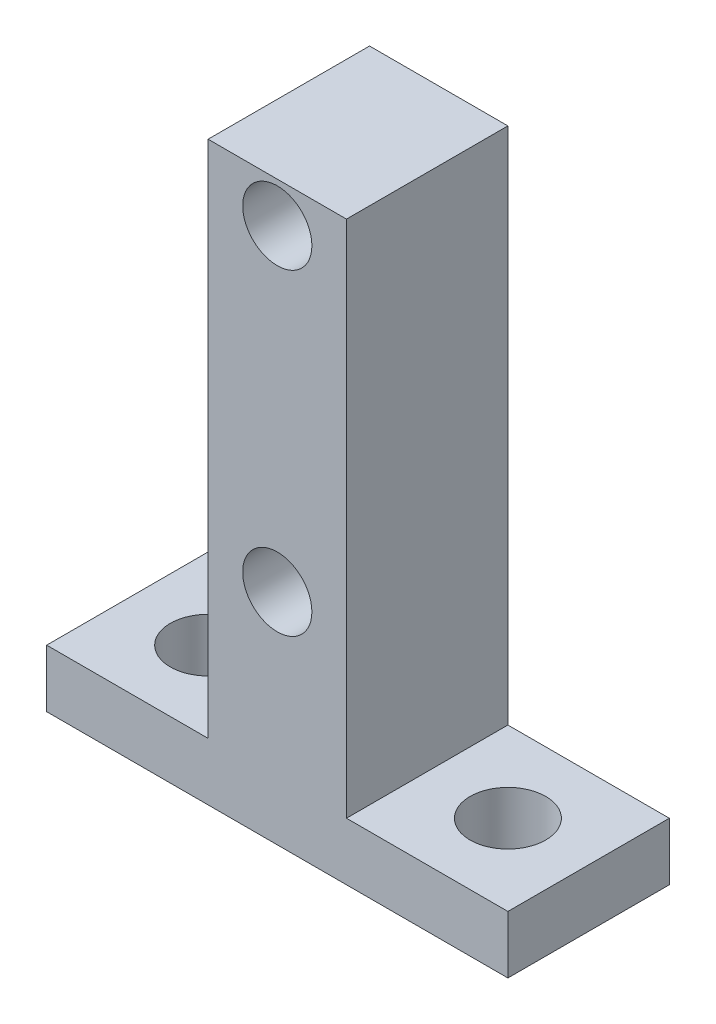
SolidWorks part; units mm, degrees
ref_plane "Front Plane" through (0, 0, 0) normal (0, 0, 1) x (1, 0, 0)
ref_plane "Top Plane" through (0, 0, 0) normal (0, 1, 0) x (1, 0, 0)
ref_plane "Right Plane" through (0, 0, 0) normal (1, 0, 0) x (0, 0, -1)
sketch "Sketch1" plane through (0, 0, 0) normal (0, 0, 1) x (1, 0, 0)
  line L0 (-37.3856, -8.255) -> (-37.3856, -3.175)
  line L1 (-37.3856, 3.175) -> (37.3856, 3.175)
  line L2 (-37.3856, 3.175) -> (-37.3856, -3.175)
  line L3 (-27.5431, -3.175) -> (37.3856, -3.175)
  line L4 (37.3856, 3.175) -> (37.3856, -3.175)
  line L5 (-37.3856, 3.175) -> (37.3856, -3.175) construction
  line L6 (-37.3856, -3.175) -> (37.3856, 3.175) construction
  line L7 (-27.5431, -8.255) -> (-27.5431, -3.175)
  circle A0 centre (-32.4644, -8.255) radius 2.3812
  arc A1 (-37.3856, -8.255) -> (-27.5431, -8.255) centre (-32.4644, -8.255) ccw
  point P0 (0, 0)
  dimension "D1" = 4.7625
  dimension "D3" = 2.54
  dimension "D2" = 6.35
  dimension "D4" = 69.85
  dimension "D5" = 5.08
extrude "Boss-Extrude1" add sketch "Sketch1" along normal blind 38.1
fillet "Fillet1" radius 6.35 1 edges at (-37.3856, 3.175, 19.05)
sketch "Sketch3" plane through (37.3856, 0, 0) normal (1, 0, 0) x (0, 0, -1)
  line L4 (0, -3.175) -> (0, 3.175)
  line L5 (0, 3.175) -> (-38.1, 3.175)
  line L6 (-38.1, 3.175) -> (-38.1, -3.175)
  line L7 (-38.1, -3.175) -> (0, -3.175)
  line L8 (0, -3.175) -> (0, 3.175)
  line L9 (0, 3.175) -> (-38.1, 3.175)
  line L10 (-38.1, 3.175) -> (-38.1, -3.175)
  line L11 (-38.1, -3.175) -> (0, -3.175)
  dimension "D1" = 0
extrude "Boss-Extrude2" add sketch "Sketch3" along normal blind 12.7
sketch "Sketch2" plane through (0, 3.175, 0) normal (0, 1, 0) x (1, 0, 0)
  line L1 (48.4981, -15.875) -> (11.9856, -15.875) construction
  line L2 (48.4981, -15.875) -> (48.4981, 0) construction
  line L3 (48.4981, 0) -> (11.9856, 0) construction
  line L4 (11.9856, -15.875) -> (11.9856, 0) construction
  line L5 (48.4981, -15.875) -> (11.9856, 0) construction
  line L6 (48.4981, 0) -> (11.9856, -15.875) construction
  line L7 (11.9856, -17.4625) -> (-16.5894, -17.4625) construction
  line L8 (11.9856, -17.4625) -> (11.9856, 1.5875) construction
  line L9 (11.9856, 1.5875) -> (-16.5894, 1.5875) construction
  line L10 (-16.5894, -17.4625) -> (-16.5894, 1.5875) construction
  line L11 (11.9856, -17.4625) -> (-16.5894, 1.5875) construction
  line L12 (11.9856, 1.5875) -> (-16.5894, -17.4625) construction
  line L13 (37.3856, -25.4) -> (37.3856, 9.525) construction
  line L14 (50.0856, 0) -> (-31.0356, 0) construction
  line L15 (-34.8456, -38.1) -> (-30.0831, -38.1) construction
  line L16 (-34.8456, -38.1) -> (-30.0831, -38.1) construction
  line L18 (21.3519, -24.765) -> (13.7319, -24.765)
  line L19 (21.3519, -24.765) -> (21.3519, -15.875)
  line L20 (21.3519, -15.875) -> (13.7319, -15.875)
  line L21 (13.7319, -24.765) -> (13.7319, -15.875)
  line L22 (21.3519, -24.765) -> (13.7319, -15.875) construction
  line L23 (21.3519, -15.875) -> (13.7319, -24.765) construction
  point P0 (30.2419, -7.9375)
  point P5 (17.5419, -20.32)
  point P6 (-2.3019, -7.9375)
  point P15 (17.5419, -20.32)
  point P21 (-32.4644, -38.1)
  point P26 (37.3856, -7.9375)
  dimension "Motor_Pos" = 15.875
  dimension "D2" = 36.5125
  dimension "D3" = 28.575
  dimension "D4" = 19.05
  dimension "D5" = 5.5562
  dimension "D6" = 11.1125
  dimension "D7" = 34.925
  dimension "D8" = 69.85
  dimension "D9" = 8.89
  dimension "D10" = 7.62
extrude "Cut-Extrude7" cut sketch "Sketch2" against normal through all
sketch "Sketch10" plane through (0, 3.175, 0) normal (0, 1, 0) x (1, 0, 0)
  line L0 (13.7319, -24.765) -> (13.7319, -15.875) construction
  line L1 (21.3519, -24.765) -> (13.7319, -24.765) construction
  line L2 (21.3519, -24.765) -> (21.3519, -15.875) construction
  line L3 (21.3519, -15.875) -> (13.7319, -15.875) construction
  line L12 (13.7319, -24.765) -> (13.7319, -15.875)
  line L13 (21.3519, -24.765) -> (13.7319, -24.765)
  line L14 (21.3519, -24.765) -> (21.3519, -15.875)
  line L15 (21.3519, -15.875) -> (13.7319, -15.875)
extrude "Boss-Extrude5" add sketch "Sketch10" along normal blind 22.225 and the other way blind 9.525
sketch "Sketch5" plane through (0, 0, 24.765) normal (0, 0, 1) x (1, 0, 0)
  line L0 (17.5419, 25.4) -> (17.5419, -6.35) construction
  line L3 (13.7319, -6.35) -> (21.3519, -6.35) construction
  line L4 (13.7319, 25.4) -> (21.3519, 25.4) construction
  circle A0 centre (17.5419, 5.715) radius 1.905
  circle A1 centre (17.5419, 23.1775) radius 1.905
  dimension "D1" = 3.81
  dimension "D2" = 17.4625
  dimension "D3" = 12.065
extrude "Cut-Extrude1" cut sketch "Sketch5" against normal through all both and the other way through all
sketch "Sketch6" plane through (0, -3.175, 0) normal (0, 1, 0) x (1, 0, 0)
  line L1 (30.2419, -24.765) -> (4.8419, -24.765)
  line L2 (30.2419, -24.765) -> (30.2419, -15.875)
  line L3 (30.2419, -15.875) -> (4.8419, -15.875)
  line L4 (4.8419, -24.765) -> (4.8419, -15.875)
  line L5 (30.2419, -24.765) -> (4.8419, -15.875) construction
  line L6 (30.2419, -15.875) -> (4.8419, -24.765) construction
  line L9 (4.8419, -24.765) -> (30.2419, -24.765) construction
  line L11 (21.3519, -15.875) -> (13.7319, -15.875) construction
  line L12 (21.3519, -24.765) -> (13.7319, -24.765) construction
  line L13 (21.3519, -24.765) -> (13.7319, -24.765)
  line L14 (13.7319, -24.765) -> (13.7319, -15.875) construction
  point P0 (17.5419, -20.32)
  point P14 (17.5419, -24.765)
  point P16 (17.5419, -24.765)
  line M22 (13.7319, -15.875) -> (13.7319, -24.765)
  line M24 (21.3519, -24.765) -> (21.3519, -15.875)
  dimension "D1" = 25.4
  dimension "D2" = 8.89
  dimension "D3" = 8.89
extrude "Boss-Extrude4" add sketch "Sketch6" against normal up to surface (3.175 mm away) contours L1 L4 L3 M22 | L3 L2 L1 M24 up to face at (17.5419, -6.35, 20.32)
sketch "Sketch7" plane through (0, -6.35, 0) normal (0, -1, 0) x (-1, 0, 0)
  line L1 (-4.8419, -24.765) -> (-13.7319, -24.765) construction
  line L2 (-4.8419, -24.765) -> (-4.8419, -15.875) construction
  line L3 (-4.8419, -15.875) -> (-13.7319, -15.875) construction
  line L4 (-13.7319, -24.765) -> (-13.7319, -15.875) construction
  line L5 (-4.8419, -24.765) -> (-13.7319, -15.875) construction
  line L6 (-4.8419, -15.875) -> (-13.7319, -24.765) construction
  line L10 (-17.5419, -24.765) -> (-17.5419, -15.875) construction
  line L12 (-4.8419, -24.765) -> (-30.2419, -24.765) construction
  line L13 (-30.2419, -15.875) -> (-4.8419, -15.875) construction
  line L14 (-4.8419, -24.765) -> (-4.8419, -15.875) construction
  line L15 (-21.3519, -24.765) -> (-21.3519, -15.875) construction
  line L16 (-13.7319, -24.765) -> (-21.3519, -24.765) construction
  line L17 (-13.7319, -15.875) -> (-13.7319, -24.765) construction
  line L18 (-21.3519, -15.875) -> (-13.7319, -15.875) construction
  line L19 (-21.3519, -24.765) -> (-21.3519, -15.875) construction
  line L20 (-13.7319, -24.765) -> (-21.3519, -24.765) construction
  line L21 (-13.7319, -15.875) -> (-13.7319, -24.765) construction
  line L22 (-21.3519, -15.875) -> (-13.7319, -15.875) construction
  circle A0 centre (-9.2869, -20.32) radius 2.0828
  circle A2 centre (-25.7969, -20.32) radius 2.0828
  point P14 (-17.5419, -24.765)
  dimension "D1" = 4.1656
extrude "Cut-Extrude2" cut sketch "Sketch7" against normal through all both and the other way through all
ref_plane "Plane1" through (-27.5431, -3.175, 38.1) normal (1, 0, 0) x (0, 0, -1)
sketch "Sketch9" plane through (0, 0, 38.1) normal (0, 0, 1) x (1, 0, 0)
  line L0 (50.0856, 3.175) -> (50.0856, -3.175) construction
  line L1 (-27.5431, -3.175) -> (50.0856, -3.175) construction
  line L2 (-27.5431, -8.255) -> (-27.5431, -3.175) construction
  line L3 (-37.3856, -3.175) -> (-37.3856, -8.255) construction
  line L4 (50.0856, 3.175) -> (-31.0356, 3.175) construction
  line L5 (50.0856, 3.175) -> (50.0856, -3.175)
  line L6 (-27.5431, -3.175) -> (50.0856, -3.175)
  line L7 (-27.5431, -8.255) -> (-27.5431, -3.175)
  line L8 (-37.3856, -3.175) -> (-37.3856, -8.255)
  line L9 (50.0856, 3.175) -> (-31.0356, 3.175)
  arc A0 (-37.3856, -8.255) -> (-27.5431, -8.255) centre (-32.4644, -8.255) ccw construction
  arc A1 (-31.0356, 3.175) -> (-37.3856, -3.175) centre (-31.0356, -3.175) ccw construction
  arc A2 (-37.3856, -8.255) -> (-27.5431, -8.255) centre (-32.4644, -8.255) ccw
  arc A3 (-31.0356, 3.175) -> (-37.3856, -3.175) centre (-31.0356, -3.175) ccw
extrude "Cut-Extrude8" cut sketch "Sketch9" against normal up to surface (13.335 mm away) up to face at (19.4469, 5.715, 24.765)
sketch "Sketch11" plane through (0, 0, 24.765) normal (0, 0, 1) x (1, 0, 0)
  line L0 (21.3519, 3.175) -> (21.3519, -3.175)
  line L1 (21.3519, -3.175) -> (30.2419, -3.175)
  line L2 (4.8419, -3.175) -> (13.7319, -3.175)
  line L3 (13.7319, -3.175) -> (13.7319, 3.175)
  line L4 (13.7319, 3.175) -> (-41.2561, 5.6638)
  line L5 (-41.2561, 5.6638) -> (-38.3082, -22.5143)
  line L6 (-38.3082, -22.5143) -> (4.8419, -3.175)
  line L7 (21.3519, 3.175) -> (51.2548, 20.6632)
  line L8 (51.2548, 20.6632) -> (54.983, -12.8037)
  line L9 (54.983, -12.8037) -> (30.2419, -3.175)
extrude "Cut-Extrude9" cut sketch "Sketch11" against normal through all
sketch "Sketch12" plane through (21.3519, 0, 0) normal (1, 0, 0) x (0, 0, -1)
  line L0 (0, -3.175) -> (-15.875, -3.175) construction
  line L1 (-15.875, 3.175) -> (0, 3.175)
  line L2 (-15.875, 3.175) -> (-15.875, -3.175)
  line L3 (-15.875, -3.175) -> (0, -3.175)
  line L4 (0, 3.175) -> (0, -3.175)
  line L5 (-15.875, 3.175) -> (0, -3.175) construction
  line L6 (-15.875, -3.175) -> (0, 3.175) construction
  line L7 (0, 3.175) -> (0, -3.175) construction
  point P4 (-7.9375, 0)
extrude "Cut-Extrude10" cut sketch "Sketch12" against normal through all
